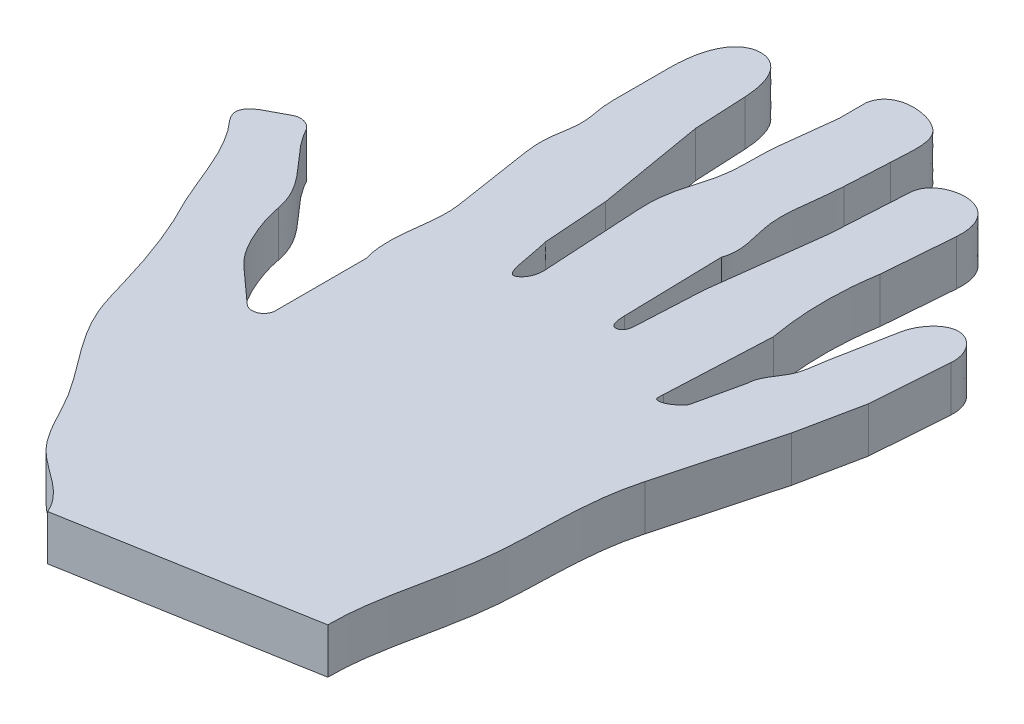
SolidWorks part; units mm, degrees
ref_plane "Front Plane" through (0, 0, 0) normal (0, 0, 1) x (1, 0, 0)
ref_plane "Top Plane" through (0, 0, 0) normal (0, 1, 0) x (1, 0, 0)
ref_plane "Right Plane" through (0, 0, 0) normal (1, 0, 0) x (0, 0, -1)
sketch "Sketch1" plane through (0, 0, 0) normal (0, 1, 0) x (1, 0, 0)
  line L0 (-39.515, 243.5) -> (220.485, 243.5) construction
  line L1 (-26.6853, 228.6112) -> (195.9814, 228.6112) construction
sketch "Sketch2" plane through (0, 0, 0) normal (0, 1, 0) x (1, 0, 0)
  line L0 (-26.2567, -4.6218) -> (26.2567, 4.6218)
  line L1 (-39.4815, 78.866) -> (-39.4815, 58.8691)
  line L2 (-51.3685, 63.7522) -> (-43.824, 56.9394)
  line L3 (-26.2567, -4.6218) -> (-14.4546, -24.7741) construction
  line L4 (-14.4546, -24.7741) -> (38.5938, -24.7741) construction
  line L5 (38.5938, -24.7741) -> (26.2567, 4.6218) construction
  line L6 (-39.4815, 53.018) -> (-26.2567, -4.6218) construction
  line L7 (33.8525, 66.9139) -> (40.7388, 92.3458)
  line L8 (40.7388, 92.3458) -> (43.6461, 106.4272)
  line L9 (43.6461, 106.4272) -> (44.8831, 123.412)
  line L10 (33.4597, 123.6603) -> (30.8741, 110.2079)
  line L11 (30.8741, 110.2079) -> (43.6461, 106.4272) construction
  line L12 (26.4015, 97.0692) -> (40.7388, 92.3458) construction
  line L13 (18.3212, 74.2909) -> (20.3699, 83.8601) construction
  line L14 (-26.2567, -4.6218) -> (-39.4815, 58.8691) construction
  line L15 (1.2395, 93.0039) -> (-0.0216, 79.1837) construction
  line L16 (-39.4815, 99.2292) -> (-41.6687, 113.3468)
  line L17 (-19.7284, 91.8229) -> (-19.3907, 80.7056) construction
  line L18 (-42.4402, 136.1897) -> (-42.4402, 148.6033)
  line L19 (-28.5502, 151.3734) -> (-27.9936, 139.9774)
  line L20 (-27.9936, 139.9774) -> (-23.9098, 115.9726)
  line L21 (-42.4402, 136.1897) -> (-27.9936, 139.9774) construction
  line L22 (-41.6687, 113.3468) -> (-23.9098, 115.9726) construction
  line L23 (-39.4815, 99.2292) -> (-22.8639, 101.6863) construction
  line L24 (-23.9098, 115.9726) -> (-22.8639, 101.6863)
  line L25 (-17.5232, 96.2681) -> (-18.8074, 118.2463)
  line L26 (-18.8074, 118.2463) -> (-0.5487, 118.2463) construction
  line L27 (-0.5487, 118.2463) -> (-0.0216, 96.2681)
  line L28 (3.0669, 95.2749) -> (3.8334, 110.2079)
  line L29 (3.8334, 110.2079) -> (6.9027, 134.5484)
  line L30 (6.9027, 134.5484) -> (7.8865, 151.3734)
  line L31 (20.1841, 132.4747) -> (21.423, 148.0183)
  line L32 (6.9027, 134.5484) -> (20.1841, 132.4747) construction
  line L33 (3.8334, 110.2079) -> (20.3699, 108.7439) construction
  line L34 (20.3699, 108.7439) -> (19.297, 85.5948)
  line L35 (-15.4372, 146.0564) -> (-14.0828, 157.6683)
  line L36 (-14.0828, 157.6683) -> (-14.0828, 163.6139)
  line L37 (-14.0828, 157.6683) -> (-0.0216, 154.9156) construction
  line L38 (-15.4372, 146.0564) -> (-0.5487, 145.2511) construction
  line L39 (24.1125, 86.8156) -> (26.4015, 97.0692)
  line L40 (-0.0216, 154.9156) -> (-0.5487, 145.2511)
  line L41 (-43.824, 56.9394) -> (-58.9055, 39.2457) construction
  line L42 (-58.832, 78.898) -> (-70.3912, 69.8292) construction
  arc A0 (-43.824, 56.9394) -> (-39.4815, 58.8691) centre (-42.0815, 58.8691) ccw
  ellipse E0 centre (-58.0967, -93.829) end of major axis (-147.8574, -255.8219) minor radius 134.063 (33.8525, 66.9139) -> (-39.4815, 78.866) ccw construction
  spline S0 degree 3 poles (26.2567, 4.6218) (26.1842, 15.0859) (31.3917, 29.8143) (31.4971, 51.0015) (32.311, 61.2207) (33.8525, 66.9139) knots 0 0 0 0 0.494425 0.733348 1 1 1 1
  spline S1 degree 3 poles (44.8831, 123.412) (45.166, 127.2965) (39.5124, 133.2479) (34.1017, 127.0003) (33.4597, 123.6603) knots 0 0 0 0 0.483944 1 1 1 1
  spline S2 degree 3 poles (30.8741, 110.2079) (30.4412, 107.9558) (30.3825, 103.3065) (26.4692, 99.7495) (26.4015, 97.0692) knots 0 0 0 0 0.456305 1 1 1 1
  spline S3 degree 3 poles (-39.4815, 78.866) (-40.9116, 83.6011) (-39.5356, 90.3331) (-39.1595, 97.1506) (-39.4815, 99.2292) knots 0 0 0 0 0.695291 1 1 1 1
  spline S4 degree 3 poles (-41.6687, 113.3468) (-42.195, 116.7435) (-42.996, 120.7947) (-40.8921, 129.1614) (-42.4402, 132.9755) (-42.4402, 136.1897) knots 0 0 0 0 0.356023 0.66976 1 1 1 1
  spline S5 degree 3 poles (-42.4402, 148.6033) (-42.4402, 156.7922) (-37.3167, 164.6528) (-28.961, 159.7826) (-28.5502, 151.3734) knots 0 0 0 0 0.532955 1 1 1 1
  spline S6 degree 2 poles (-41.6158, 128.6497) (-33.9419, 125.9932) (-26.2567, 129.7679) knots 0 0 0 1 1 1 construction
  spline S7 degree 2 poles (20.3699, 108.7439) (18.2513, 120.5692) (20.1841, 132.4747) knots 0 0 0 1 1 1
  spline S8 degree 3 poles (-18.8074, 118.2463) (-18.9824, 121.242) (-18.4553, 126.1045) (-15.1652, 135.2192) (-15.9522, 141.6411) (-15.4372, 146.0564) knots 0 0 0 0 0.292833 0.552751 1 1 1 1
  spline S9 degree 3 poles (19.297, 85.5948) (19.2433, 84.4361) (19.0942, 83.7796) (20.9409, 83.8488) (22.4328, 84.7912) (23.9346, 86.019) (24.1125, 86.8156) knots 0 0 0 0 0.237089 0.343165 0.637099 1 1 1 1
  spline S10 degree 3 poles (-0.0216, 96.2681) (0.0277, 94.2134) (0.699, 92.1431) (2.9809, 93.5986) (3.0669, 95.2749) knots 0 0 0 0 0.545551 1 1 1 1
  spline S11 degree 3 poles (-17.5232, 96.2681) (-17.4786, 95.5044) (-17.6633, 93.4711) (-20.6935, 90.5303) (-21.7417, 96.3035) (-22.9071, 102.2765) (-22.8639, 101.6863) knots 0 0 0 0 0.194417 0.332419 0.645496 1 1 1 1
  spline S12 degree 3 poles (-14.0828, 163.6139) (-13.2063, 169.2957) (1.2712, 168.2301) (0.2952, 160.7246) (-0.0216, 154.9156) knots 0 0 0 0 0.553573 1 1 1 1
  spline S13 degree 3 poles (7.8865, 151.3734) (8.0614, 154.3654) (14.8466, 158.8319) (21.952, 154.6558) (21.423, 148.0183) knots 0 0 0 0 0.394994 1 1 1 1
  spline S14 degree 3 poles (-0.5487, 145.2511) (-0.9153, 138.529) (-3.2108, 131.2708) (0.7563, 121.8169) (-0.5487, 118.2463) knots 0 0 0 0 0.597213 1 1 1 1
  spline S15 degree 3 poles (-26.2567, -4.6218) (-28.6067, 0.8925) (-39.2709, 4.8688) (-44.8505, 18.8756) (-52.8032, 28.8167) (-57.3456, 35.5284) (-58.9055, 39.2457) knots 0 0 0 0 0.306365 0.556646 0.785775 1 1 1 1
  spline S16 degree 3 poles (-58.832, 78.898) (-58.301, 75.9589) (-56.3707, 70.4369) (-53.4093, 65.595) (-51.3685, 63.7522) knots 0 0 0 0 0.533943 1 1 1 1
  spline S17 degree 3 poles (-58.832, 78.898) (-59.4781, 82.4734) (-63.456, 88.1907) (-68.8643, 93.3388) (-71.1877, 97.8175) (-73.6577, 98.7992) (-78.0903, 96.0626) (-83.8518, 94.1525) (-80.9801, 90.259) knots 0 0 0 0 0.267503 0.557707 0.58268 0.669255 0.724556 1 1 1 1
  spline S18 degree 3 poles (-80.9801, 90.259) (-75.7387, 84.47) (-73.6189, 76.772) (-70.3912, 69.8292) knots 0 0 0 0 1 1 1 1
  spline S19 degree 3 poles (-70.3912, 69.8292) (-66.692, 62.8605) (-62.867, 52.5433) (-60.0866, 42.0604) (-58.9055, 39.2457) knots 0 0 0 0 0.723669 1 1 1 1
  point P4 (0, 0)
  point P15 (-19.3907, 80.7056)
  point P18 (-0.0216, 79.1837)
  point P22 (18.3212, 74.2909)
  dimension "D1" = 2.6
extrude "Boss-Extrude1" add sketch "Sketch2" along normal mid plane 10
equation "\"x\"= 1mm'for scaling"
equation "\"D1@Sketch2\"=2.6*\"x\""
